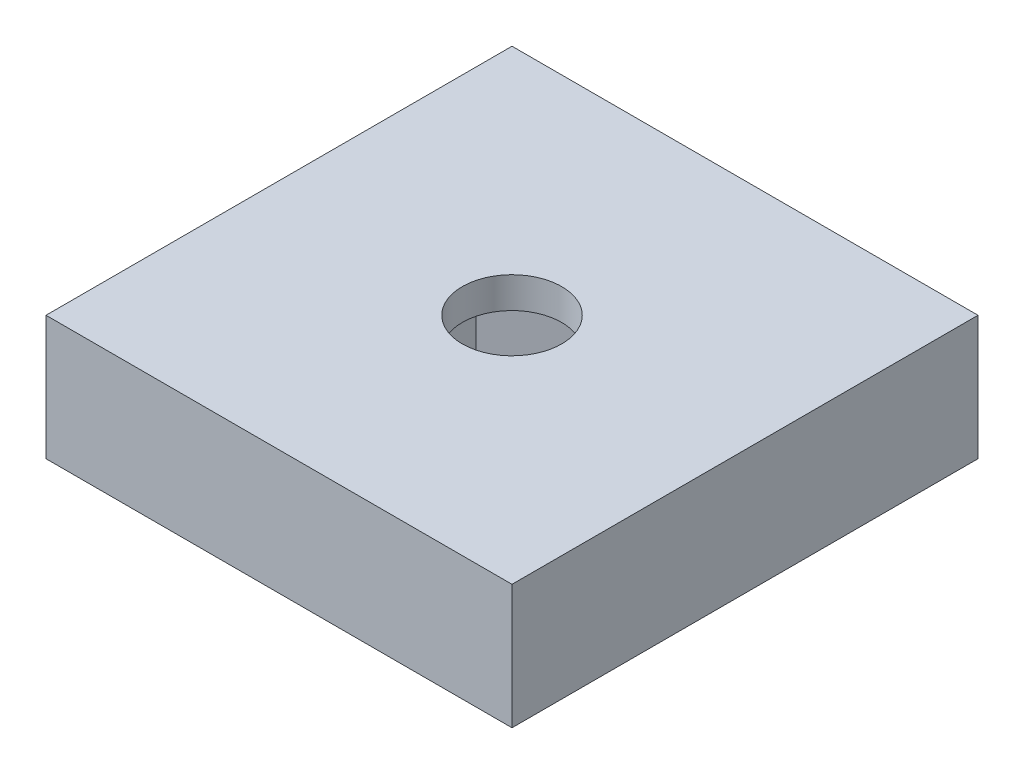
SolidWorks part; units mm, degrees
ref_plane "Alzado" through (0, 0, 0) normal (0, 0, 1) x (1, 0, 0)
ref_plane "Planta" through (0, 0, 0) normal (0, 1, 0) x (1, 0, 0)
ref_plane "Vista lateral" through (0, 0, 0) normal (1, 0, 0) x (0, 0, -1)
sketch "Croquis1" plane through (0, 0, 0) normal (0, 1, 0) x (1, 0, 0)
  line L0 (0, 15) -> (15, 0) construction
  line L1 (0, 0) -> (15, 0)
  line L2 (0, 0) -> (0, 15)
  line L3 (0, 15) -> (15, 15)
  line L4 (15, 0) -> (15, 15)
  circle A0 centre (7.5, 7.5) radius 1.6
  dimension "D2" = 3.2
  dimension "D1" = 15
extrude "Saliente-Extruir1" add sketch "Croquis1" along normal blind 3
sketch "Croquis2" plane through (0, 3, 0) normal (0, 1, 0) x (1, 0, 0)
  line L0 (7.5, 4.3246) -> (7.5, 7.5) construction
  line L1 (7.5, 4.3246) -> (10.25, 5.9123)
  line L2 (10.25, 5.9123) -> (10.25, 9.0877)
  line L3 (10.25, 9.0877) -> (7.5, 10.6754)
  line L4 (7.5, 10.6754) -> (4.75, 9.0877)
  line L5 (4.75, 9.0877) -> (4.75, 5.9123)
  line L6 (4.75, 5.9123) -> (7.5, 4.3246)
  circle A0 centre (7.5, 7.5) radius 2.75 construction
  dimension "D1" = 5.5
extrude "Cortar-Extruir1" cut sketch "Croquis2" against normal blind 2.3
sketch "Croquis3" plane through (0, 3, 0) normal (0, 1, 0) x (1, 0, 0)
  line L4 (0, 15) -> (0, 0)
  line L5 (0, 0) -> (15, 0)
  line L6 (15, 0) -> (15, 15)
  line L7 (15, 15) -> (0, 15)
  line L8 (0, 15) -> (0, 0)
  line L9 (0, 0) -> (15, 0)
  line L10 (15, 0) -> (15, 15)
  line L11 (15, 15) -> (0, 15)
  circle A0 centre (7.5, 7.5) radius 1.6 construction
  circle A1 centre (7.5, 7.5) radius 1.6
  dimension "D1" = 0
extrude "Saliente-Extruir2" add sketch "Croquis3" along normal blind 1
